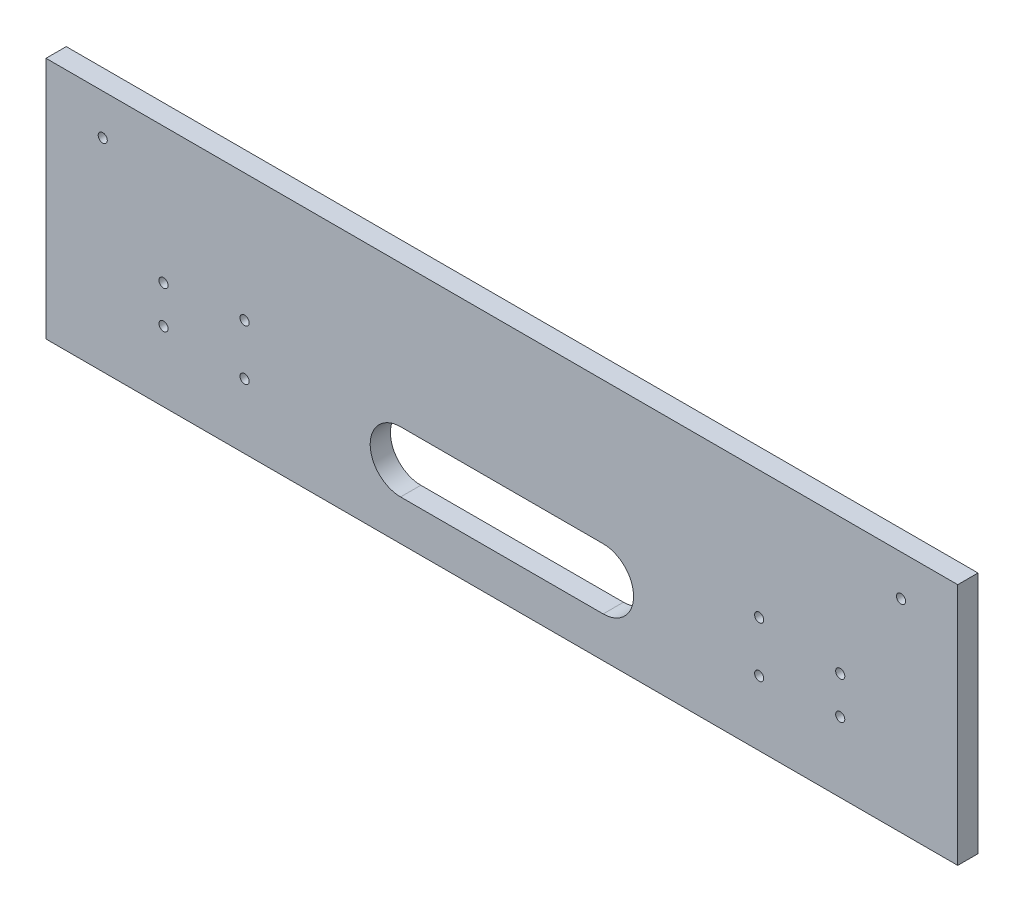
SolidWorks part; units mm, degrees
material "Multistrato di pioppo"
ref_plane "Piano frontale" through (0, 0, 0) normal (0, 0, 1) x (1, 0, 0)
ref_plane "Piano superiore" through (0, 0, 0) normal (0, 1, 0) x (1, 0, 0)
ref_plane "Piano destro" through (0, 0, 0) normal (1, 0, 0) x (0, 0, -1)
sketch "Schizzo1" plane through (0, 0, 0) normal (0, 0, 1) x (1, 0, 0)
  line L1 (-225, 60) -> (225, 60)
  line L2 (-225, 60) -> (-225, -60)
  line L3 (-225, -60) -> (225, -60)
  line L4 (225, 60) -> (225, -60)
  line L5 (-225, 60) -> (225, -60) construction
  line L6 (-225, -60) -> (225, 60) construction
  point P4 (0, 0)
  dimension "D1" = 120
  dimension "D2" = 450
extrude "Estrusione-Estrusione1" add sketch "Schizzo1" along normal blind 10
sketch "Schizzo2" plane through (0, 0, 0) normal (0, 0, -1) x (-1, 0, 0)
  line L0 (0, 0) -> (0, -25) construction
  line L5 (225, -60) -> (-225, -60) construction
  line L6 (-50, -25) -> (50, -25) construction
  line L7 (-50, -10) -> (50, -10)
  line L8 (-50, -40) -> (50, -40)
  arc A0 (-50, -10) -> (-50, -40) centre (-50, -25) ccw
  arc A1 (50, -40) -> (50, -10) centre (50, -25) ccw
  point P11 (0, -25)
  dimension "D5" = 130
  dimension "D4" = 20
  dimension "D6" = 30
extrude "Taglio-Estrusione1" cut sketch "Schizzo2" against normal blind 10
sketch "Schizzo3" plane through (0, 0, 10) normal (0, 0, 1) x (1, 0, 0)
  line L0 (127, -25) -> (127, -2) construction
  line L1 (-225, -60) -> (225, -60) construction
  line L2 (225, -60) -> (225, 60) construction
  line L3 (-127, -2) -> (-127, -25) construction
  line L4 (-197, 40) -> (197, 40) construction
  line L5 (-225, 60) -> (-225, -60) construction
  line L6 (-225, -60) -> (225, -60) construction
  line L7 (225, 60) -> (-225, 60) construction
  circle A0 centre (-167, -7) radius 2.25
  circle A1 centre (-167, -25.5) radius 2.25
  circle A2 centre (167, -7) radius 2.25
  circle A3 centre (167, -25.5) radius 2.25
  circle A5 centre (197, 40) radius 2.25
  circle A7 centre (-197, 40) radius 2.25
  circle A8 centre (127, -2) radius 2.25 construction
  circle A9 centre (127, -25) radius 2.25 construction
  circle A10 centre (-127, -2) radius 2.25 construction
  circle A11 centre (-127, -25) radius 2.25 construction
  point P19 (224.2131, 65.6624)
  dimension "D1" = 4.5
  dimension "D5" = 4.5
  dimension "D2" = 23
  dimension "D3" = 58
  dimension "D4" = 98
  dimension "D6" = 98
  dimension "D7" = 58
  dimension "D8" = 20
  dimension "D9" = 28
  dimension "D10" = 28
extrude "Taglio-Estrusione2" cut sketch "Schizzo3" against normal blind 10
sketch "Schizzo4" plane through (0, 0, 0) normal (0, 0, -1) x (-1, 0, 0)
  line L0 (-127, -28) -> (-127, -3) construction
  line L1 (127, -28) -> (127, -3) construction
  line L2 (-225, -60) -> (-225, 60) construction
  line L3 (225, -60) -> (-225, -60) construction
  line L4 (225, 60) -> (225, -60) construction
  circle A0 centre (-127, -3) radius 2.25
  circle A1 centre (-127, -28) radius 2.25
  circle A2 centre (127, -28) radius 2.25
  circle A3 centre (127, -3) radius 2.25
  dimension "D1" = 4.5
  dimension "D2" = 25
  dimension "D3" = 98
  dimension "D4" = 32
  dimension "D5" = 25
  dimension "D6" = 98
  dimension "D7" = 32
extrude "Taglio-Estrusione3" cut sketch "Schizzo4" against normal blind 10
